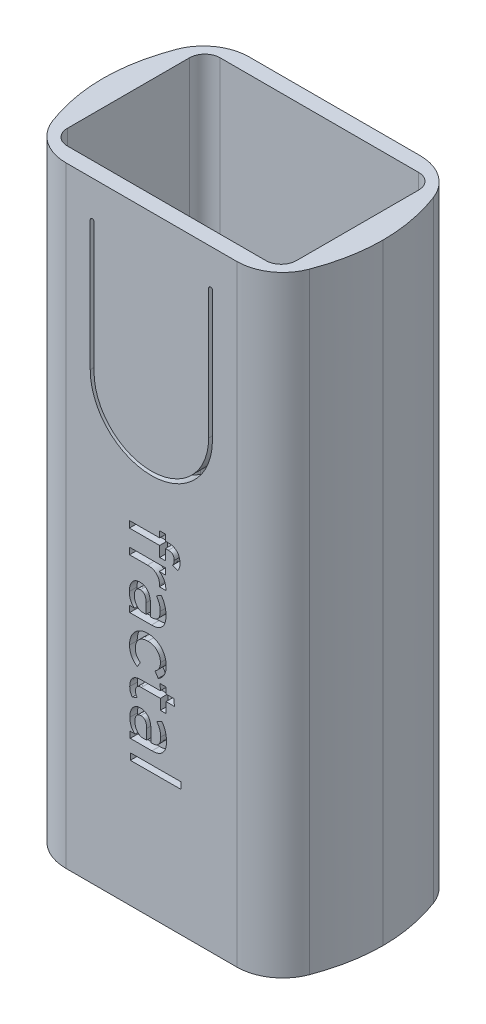
SolidWorks part; units mm, degrees
ref_plane "Front Plane" through (0, 0, 0) normal (0, 0, 1) x (1, 0, 0)
ref_plane "Top Plane" through (0, 0, 0) normal (0, 1, 0) x (1, 0, 0)
ref_plane "Right Plane" through (0, 0, 0) normal (1, 0, 0) x (0, 0, -1)
ref_plane "Plane1" through (0, 58, 0) normal (0, 1, 0) x (1, 0, 0)
sketch "Sketch8" plane through (0, 58, 0) normal (0, 1, 0) x (1, 0, 0)
  line L1 (-15, -8) -> (-15, 8)
  line L2 (-13, 10) -> (13, 10)
  line L5 (-15, 10) -> (-14.2911, 9.5274) construction
  line L8 (-11.1948, 12) -> (11.1948, 12)
  line L11 (-15.4079, 10.272) -> (-14.2911, 9.5274) construction
  line L12 (15.4079, 10.272) -> (14.2911, 9.5274) construction
  line L15 (0, 12) -> (0, -12) construction
  line L16 (15, 10) -> (14.2911, 9.5274) construction
  line L17 (15, -8) -> (15, 8)
  line L18 (15, -10) -> (14.2911, -9.5274) construction
  line L19 (15.4079, -10.272) -> (14.2911, -9.5274) construction
  line L20 (-18.3347, 0) -> (18.3347, 0) construction
  line L21 (0, 0) -> (0, 12) construction
  line L22 (-15.4079, -10.272) -> (-14.2911, -9.5274) construction
  line L23 (-15, -10) -> (-14.2911, -9.5274) construction
  line L24 (-11.1948, -12) -> (11.1948, -12)
  line L25 (-13, -10) -> (13, -10)
  arc A8 (-13, 10) -> (-15, 8) centre (-13, 8) ccw
  arc A10 (-11.1948, 12) -> (-16.8117, 8.1097) centre (-11.1948, 6) ccw
  arc A11 (11.1948, 12) -> (16.8117, 8.1097) centre (11.1948, 6) cw
  arc A12 (13, 10) -> (15, 8) centre (13, 8) cw
  arc A13 (13, -10) -> (15, -8) centre (13, -8) ccw
  arc A14 (11.1948, -12) -> (16.8117, -8.1097) centre (11.1948, -6) ccw
  arc A15 (-11.1948, -12) -> (-16.8117, -8.1097) centre (-11.1948, -6) cw
  arc A16 (-13, -10) -> (-15, -8) centre (-13, -8) cw
  spline S0 degree 3 poles (-18.3347, 0) (-18.3272, 2.7261) (-17.8195, 5.4265) (-16.8117, 8.1097) knots 0.502499 0.502499 0.502499 0.502499 0.837905 0.837905 0.837905 0.837905
  spline S1 degree 3 poles (18.3347, 0) (18.3272, 2.7261) (17.8195, 5.4265) (16.8117, 8.1097) knots 0.502499 0.502499 0.502499 0.502499 0.837905 0.837905 0.837905 0.837905
  spline S2 degree 3 poles (18.3347, 0) (18.3272, -2.7261) (17.8195, -5.4265) (16.8117, -8.1097) knots 0.502499 0.502499 0.502499 0.502499 0.837905 0.837905 0.837905 0.837905
  spline S3 degree 3 poles (-18.3347, 0) (-18.3272, -2.7261) (-17.8195, -5.4265) (-16.8117, -8.1097) knots 0.502499 0.502499 0.502499 0.502499 0.837905 0.837905 0.837905 0.837905
  point P0 (0, 0)
  point P8 (-15, 0)
  point P19 (-15, 10)
  point P26 (0, 0)
  point P27 (-12, 9.5)
  point P36 (0, 10)
  point P37 (12, 9.5)
  point P51 (-18.3347, 0)
  point P53 (-15, 0)
  point P55 (12, -9.5)
  point P61 (15, 0)
  point P62 (0, -10)
  point P63 (-12, -9.5)
  dimension "D3" = 8.2959
  dimension "D6" = 3.8903
  dimension "D2" = 6
  dimension "D7" = 2
  dimension "D1" = 13.9635
  dimension "D4" = 3.3347
  dimension "D5" = 1.523
  dimension "D8" = 2
  dimension "D9" = 15
sketch "Sketch11" plane through (0, 58, 0) normal (0, 1, 0) x (1, 0, 0)
  line L10 (-13, 10) -> (13, 10) construction
  line L11 (13, 10) -> (15, 10)
  line L13 (-13, 7.4379) -> (-13, 10)
  line L19 (15, 10) -> (15, 6.9379)
  line L20 (15, 6.9379) -> (13.5, 6.9379)
  line L21 (13, 7.4379) -> (13, 10)
  line L22 (-15, 6.9379) -> (-13.5, 6.9379)
  line L23 (-15, 10) -> (-15, 6.9379)
  line L24 (-13, 10) -> (-15, 10)
  arc A4 (13.5, 6.9379) -> (13, 7.4379) centre (13.5, 7.4379) cw
  arc A5 (-13.5, 6.9379) -> (-13, 7.4379) centre (-13.5, 7.4379) ccw
  dimension "D1" = 0.5
extrude "Boss-Extrude4" add sketch "Sketch8" along normal blind 80
extrude "Boss-Extrude5" add sketch "Sketch11" along normal blind 57
sketch "Sketch12" plane through (0, 0, 12) normal (0, 0, 1) x (1, 0, 0)
  line L1 (0, 116.1342) -> (0, 135.2209) construction
  line L2 (7.5, 133.1342) -> (7.5, 116.1342)
  line L3 (-7.5, 133.1342) -> (-7.5, 116.1342)
  line L4 (8, 133.1342) -> (8, 116.1342)
  line L5 (-8, 116.1342) -> (-8, 133.1342)
  line L6 (7.5, 130.5553) -> (0, 130.5553) construction
  line L7 (0, 130.5553) -> (-7.5, 130.5553) construction
  line L8 (-11.1948, 138) -> (11.1948, 138) construction
  line L9 (0, 138) -> (0, 58) construction
  line L10 (13.2, 58) -> (-13.2, 58) construction
  arc A1 (8, 116.1342) -> (-8, 116.1342) centre (0, 116.1342) cw
  arc A2 (7.5, 133.1342) -> (8, 133.1342) centre (7.75, 133.1342) cw
  arc A3 (-8, 133.1342) -> (-7.5, 133.1342) centre (-7.75, 133.1342) cw
  arc A4 (7.5, 116.1342) -> (-7.5, 116.1342) centre (0, 116.1342) cw
  point P1 (0, 108.6342)
  point P14 (0, 108.1342)
  point P20 (0.4953, 108.6342)
  point P23 (0, 138)
  dimension "D5" = 0.5
  dimension "D1" = 15
  dimension "D2" = 0.5
  dimension "D3" = 0.5
  dimension "D4" = 25
  dimension "D7" = 4.6657
extrude "Cut-Extrude1" cut sketch "Sketch12" against normal blind 2
sketch "Sketch13" plane through (0, 0, 12) normal (0, 0, 1) x (1, 0, 0)
  line L0 (-2.8774, 102.535) -> (-2.7121, 66.7717) construction
  text T0 "fractal" font "Montserrat Medium" height in points 24
extrude "Cut-Extrude2" cut sketch "Sketch13" against normal blind 1
